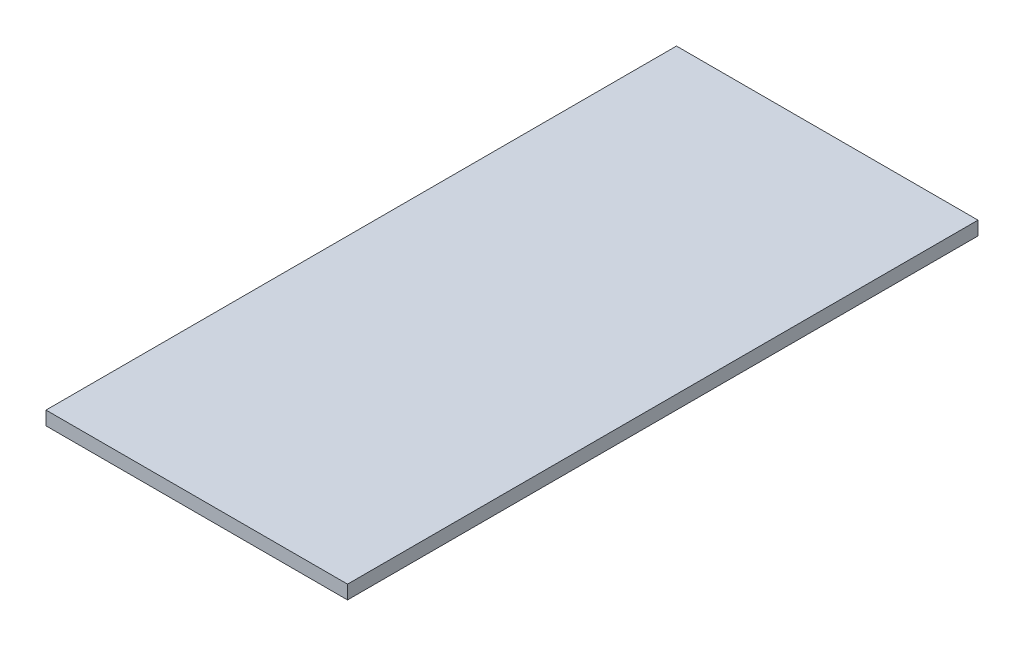
SolidWorks part; units mm, degrees
ref_plane "Front Plane" through (0, 0, 0) normal (0, 0, 1) x (1, 0, 0)
ref_plane "Top Plane" through (0, 0, 0) normal (0, 1, 0) x (1, 0, 0)
ref_plane "Right Plane" through (0, 0, 0) normal (1, 0, 0) x (0, 0, -1)
sketch "Sketch1" plane through (0, 0, 0) normal (0, 1, 0) x (1, 0, 0)
  line L0 (-139.7, -292.1) -> (139.7, 292.1) construction
  line L1 (-139.7, 292.1) -> (139.7, 292.1)
  line L2 (-139.7, 292.1) -> (-139.7, -292.1)
  line L3 (-139.7, -292.1) -> (139.7, -292.1)
  line L4 (139.7, 292.1) -> (139.7, -292.1)
  line L5 (0, 0) -> (0, 232.3863) construction
  line L6 (0, 0) -> (300.98, 0) construction
  line L8 (-381, 381) -> (381, 381)
  line L9 (-381, 381) -> (-381, -381)
  line L10 (-381, -381) -> (381, -381)
  line L11 (381, 381) -> (381, -381)
  point P4 (0, 0)
  point P14 (0, 0)
  dimension "D1" = 584.2
  dimension "D2" = 279.4
  dimension "D3" = 762
extrude "Boss-Extrude1" add sketch "Sketch1" along normal blind 12.7
